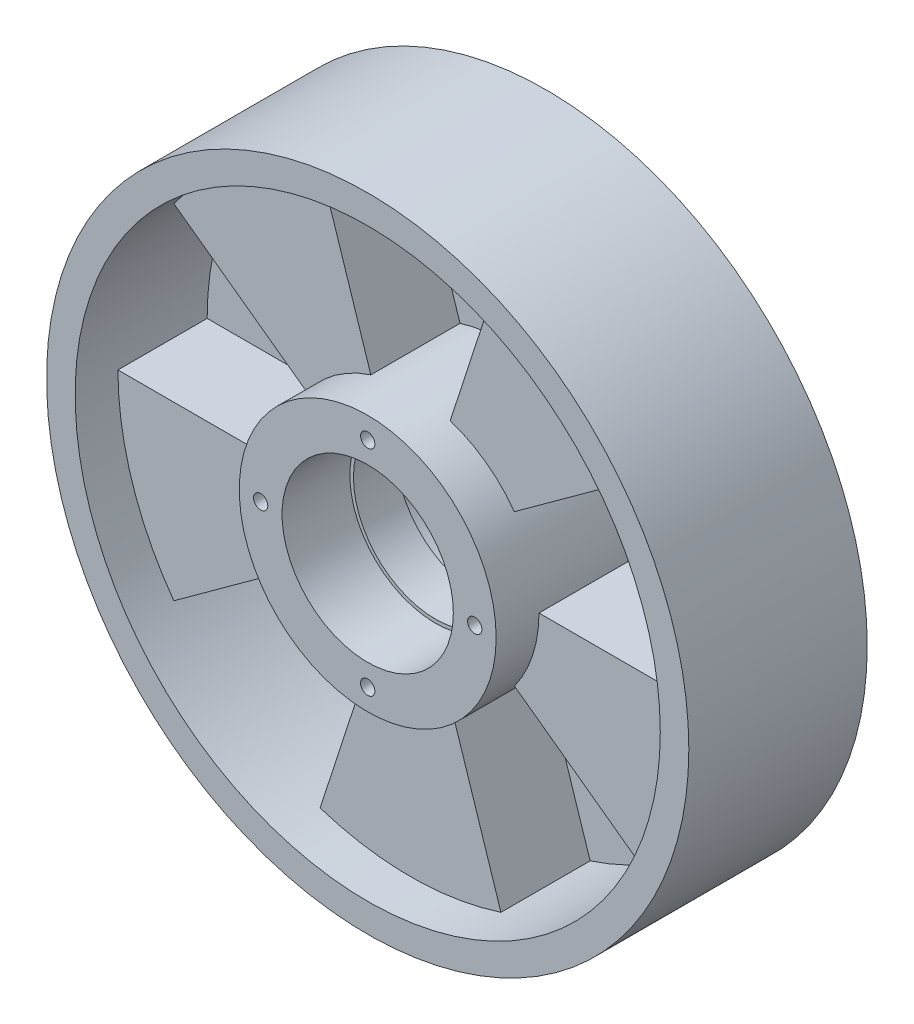
SolidWorks part; units mm, degrees
material "Nylon 101"
ref_plane "Front Plane" through (0, 0, 0) normal (0, 0, 1) x (1, 0, 0)
ref_plane "Top Plane" through (0, 0, 0) normal (0, 1, 0) x (1, 0, 0)
ref_plane "Right Plane" through (0, 0, 0) normal (1, 0, 0) x (0, 0, -1)
sketch "Sketch1" plane through (0, 0, 0) normal (0, 0, 1) x (1, 0, 0)
  circle A0 centre (0, 0) radius 90
extrude "Boss-Extrude1" add sketch "Sketch1" along normal mid plane 50
sketch "Sketch3" plane through (0, 0, 25) normal (0, 0, 1) x (1, 0, 0)
  circle A0 centre (0, 0) radius 24
extrude "Cut-Extrude2" cut sketch "Sketch3" against normal blind 19
sketch "Sketch4" plane through (0, 0, -25) normal (0, 0, -1) x (-1, 0, 0)
  circle A0 centre (0, 0) radius 24
extrude "Cut-Extrude3" cut sketch "Sketch4" against normal blind 19
sketch "Sketch5" plane through (0, 0, -6) normal (0, 0, -1) x (-1, 0, 0)
  circle A0 centre (0, 0) radius 23
extrude "Cut-Extrude4" cut sketch "Sketch5" against normal blind 12
sketch "Sketch6" plane through (0, 0, -25) normal (0, 0, -1) x (-1, 0, 0)
  circle A0 centre (0, 0) radius 36
  circle A1 centre (0, 0) radius 82
extrude "Cut-Extrude7" cut sketch "Sketch6" against normal blind 12
sketch "Sketch8" plane through (0, 0, 25) normal (0, 0, 1) x (1, 0, 0)
  circle A0 centre (0, 0) radius 36
  circle A1 centre (0, 0) radius 82
extrude "Cut-Extrude8" cut sketch "Sketch8" against normal blind 12
sketch "Sketch11" plane through (0, 0, 13) normal (0, 0, 1) x (1, 0, 0)
  line L1 (11.1246, 34.238) -> (25.3394, 77.9866)
  line L2 (-11.1246, 34.238) -> (-25.3394, 77.9866)
  line L3 (29.1246, 21.1603) -> (66.3394, 48.1984)
  line L4 (36, 0) -> (82, 0)
  line L5 (29.1246, -21.1603) -> (66.3394, -48.1984)
  line L6 (11.1246, -34.238) -> (25.3394, -77.9866)
  line L7 (-11.1246, -34.238) -> (-25.3394, -77.9866)
  line L8 (-29.1246, -21.1603) -> (-66.3394, -48.1984)
  line L9 (-36, 0) -> (-82, 0)
  line L10 (-29.1246, 21.1603) -> (-66.3394, 48.1984)
  circle A0 centre (0, 0) radius 82 construction
  arc A1 (11.1246, 34.238) -> (-11.1246, 34.238) centre (0, 0) ccw
  arc A2 (25.3394, 77.9866) -> (-25.3394, 77.9866) centre (0, 0) ccw
  arc A3 (36, 0) -> (29.1246, 21.1603) centre (0, 0) ccw
  arc A4 (82, 0) -> (66.3394, 48.1984) centre (0, 0) ccw
  arc A5 (11.1246, -34.238) -> (29.1246, -21.1603) centre (0, 0) ccw
  arc A6 (25.3394, -77.9866) -> (66.3394, -48.1984) centre (0, 0) ccw
  arc A7 (-29.1246, -21.1603) -> (-11.1246, -34.238) centre (0, 0) ccw
  arc A8 (-66.3394, -48.1984) -> (-25.3394, -77.9866) centre (0, 0) ccw
  arc A9 (-29.1246, 21.1603) -> (-36, 0) centre (0, 0) ccw
  arc A10 (-66.3394, 48.1984) -> (-82, 0) centre (0, 0) ccw
  point P29 (0, 0)
  dimension "D1" = 5
extrude "Cut-Extrude10" cut sketch "Sketch11" against normal blind 25
sketch "Sketch12" plane through (0, 0, -13) normal (0, 0, -1) x (-1, 0, 0)
  line L0 (11.7205, 34.0387) -> (26.6966, 77.5325)
  line L3 (28.7509, 21.6653) -> (65.4881, 49.3488)
  line L4 (35.9945, -0.6283) -> (81.9875, -1.4311)
  line L5 (29.4895, -20.6488) -> (67.1705, -47.0333)
  line L6 (10.5254, -34.427) -> (23.9745, -78.417)
  line L7 (-10.5254, -34.427) -> (-23.9745, -78.417)
  line L8 (-29.4895, -20.6488) -> (-67.1705, -47.0333)
  line L9 (-35.9945, -0.6283) -> (-81.9875, -1.4311)
  line L10 (-28.7509, 21.6653) -> (-65.4881, 49.3488)
  line L11 (-11.7205, 34.0387) -> (-26.6966, 77.5325)
  arc A1 (28.7509, 21.6653) -> (11.7205, 34.0387) centre (0, 0) ccw
  arc A2 (65.4881, 49.3488) -> (26.6966, 77.5325) centre (0, 0) ccw
  arc A3 (28.7509, 21.6653) -> (11.7205, 34.0387) centre (0, 0) ccw
  arc A4 (67.1705, -47.0333) -> (81.9875, -1.4311) centre (0, 0) ccw
  arc A5 (29.4895, -20.6488) -> (35.9945, -0.6283) centre (0, 0) ccw
  arc A6 (-23.9745, -78.417) -> (23.9745, -78.417) centre (0, 0) ccw
  arc A7 (-10.5254, -34.427) -> (10.5254, -34.427) centre (0, 0) ccw
  arc A8 (-81.9875, -1.4311) -> (-67.1705, -47.0333) centre (0, 0) ccw
  arc A9 (-35.9945, -0.6283) -> (-29.4895, -20.6488) centre (0, 0) ccw
  arc A10 (-26.6966, 77.5325) -> (-65.4881, 49.3488) centre (0, 0) ccw
  arc A11 (-11.7205, 34.0387) -> (-28.7509, 21.6653) centre (0, 0) ccw
  point P24 (0, 0)
  circle M1 centre (0, 0) radius 36
  circle M2 centre (0, 0) radius 82
  dimension "D1" = 5
extrude "Cut-Extrude11" cut sketch "Sketch12" against normal blind 25 contours L11 L10 M1 M2 | L3 L0 M1 M2 | L5 L4 M1 M2 | L9 L8 M1 M2 | L7 L6 M1 M2
sketch "Sketch13" plane through (0, 0, -25) normal (0, 0, -1) x (-1, 0, 0)
  circle A1 centre (0, 30) radius 2
  circle A2 centre (30, 0) radius 2
  circle A3 centre (0, -30) radius 2
  circle A4 centre (-30, 0) radius 2
extrude "Cut-Extrude12" cut sketch "Sketch13" against normal through all
